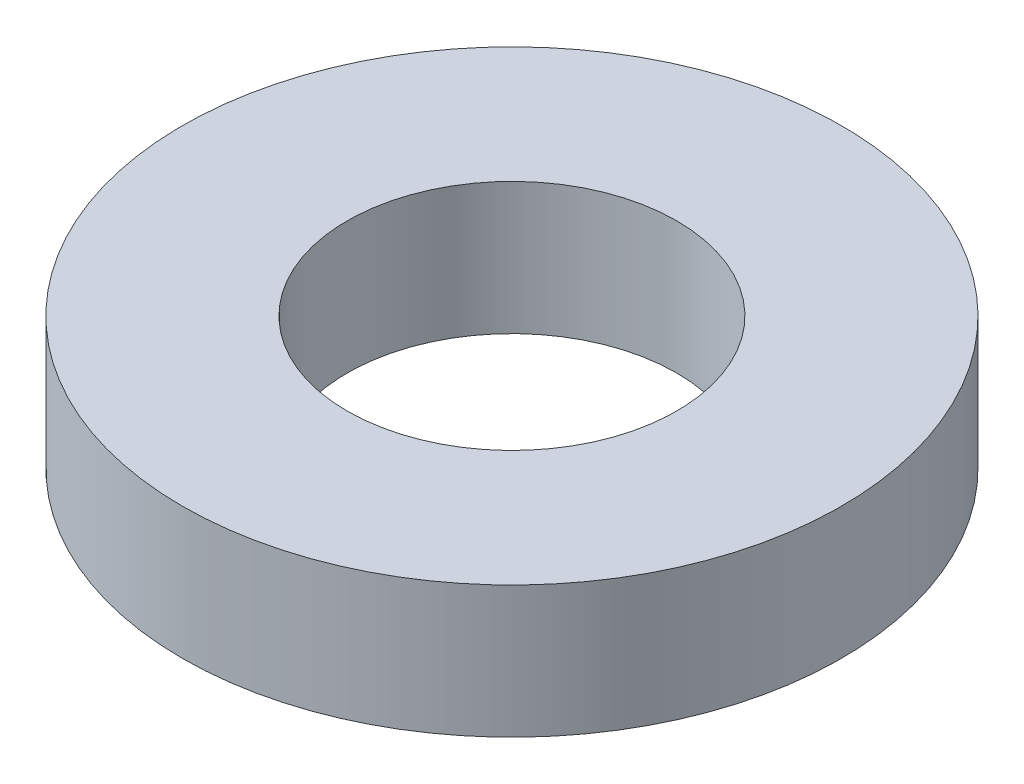
SolidWorks part; units mm, degrees
material "Nylon 101"
ref_plane "Front Plane" through (0, 0, 0) normal (0, 0, 1) x (1, 0, 0)
ref_plane "Top Plane" through (0, 0, 0) normal (0, 1, 0) x (1, 0, 0)
ref_plane "Right Plane" through (0, 0, 0) normal (1, 0, 0) x (0, 0, -1)
sketch "Sketch1" plane through (0, 0, 0) normal (0, 1, 0) x (1, 0, 0)
  circle A0 centre (0, 0) radius 6.35
  dimension "D1" = 12.7
extrude "Boss-Extrude1" add sketch "Sketch1" along normal blind 2.54
sketch "Sketch2" plane through (0, 2.54, 0) normal (0, 1, 0) x (1, 0, 0)
  circle A0 centre (0, 0) radius 3.175
  dimension "D1" = 6.35
extrude "Cut-Extrude1" cut sketch "Sketch2" against normal up to surface (2.54 mm away) up to face at (0, 0, 6.35)
